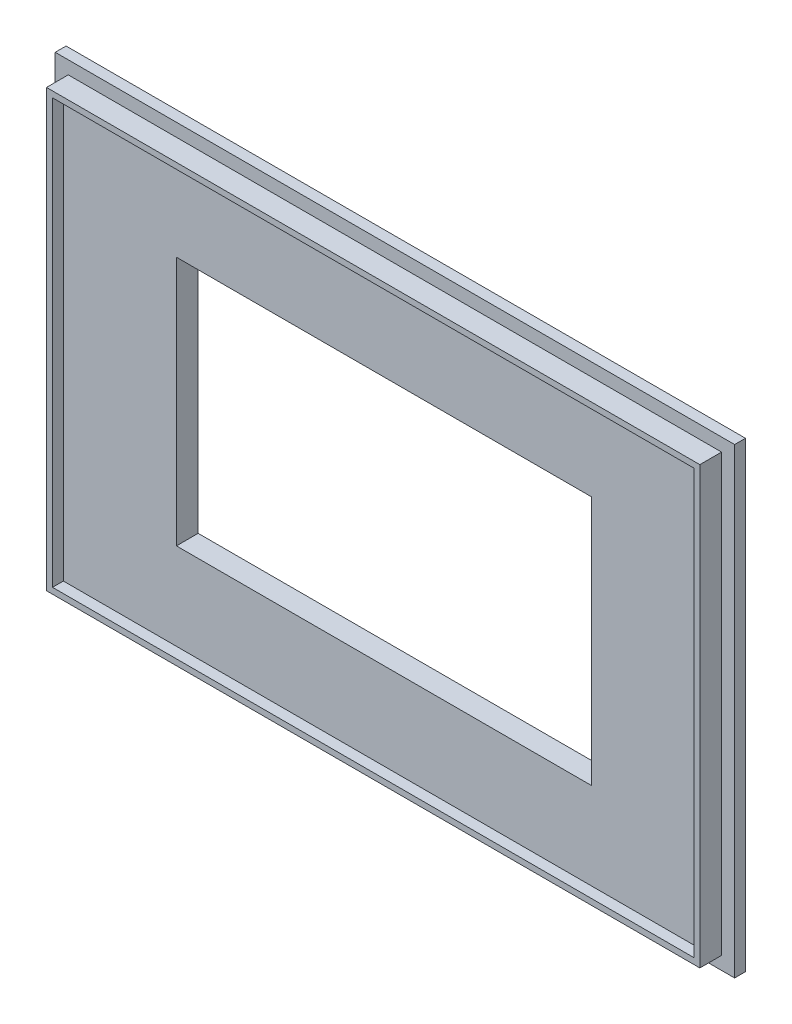
SolidWorks part; units mm, degrees
ref_plane "Front Plane" through (0, 0, 0) normal (0, 0, 1) x (1, 0, 0)
ref_plane "Top Plane" through (0, 0, 0) normal (0, 1, 0) x (1, 0, 0)
ref_plane "Right Plane" through (0, 0, 0) normal (1, 0, 0) x (0, 0, -1)
sketch "Sketch1" plane through (0, 0, 0) normal (0, 0, 1) x (1, 0, 0)
  line L1 (-79.375, -53.975) -> (79.375, -53.975)
  line L2 (-79.375, -53.975) -> (-79.375, 53.975)
  line L3 (-79.375, 53.975) -> (79.375, 53.975)
  line L4 (79.375, -53.975) -> (79.375, 53.975)
  line L5 (-79.375, -53.975) -> (79.375, 53.975) construction
  line L6 (-79.375, 53.975) -> (79.375, -53.975) construction
  point P0 (0, 0)
  dimension "D1" = 158.75
  dimension "D2" = 107.95
extrude "Boss-Extrude1" add sketch "Sketch1" along normal blind 2.54
sketch "Sketch2" plane through (0, 0, 2.54) normal (0, 0, 1) x (1, 0, 0)
  line L1 (-76.327, -50.927) -> (76.327, -50.927)
  line L2 (-76.327, -50.927) -> (-76.327, 50.927)
  line L3 (-76.327, 50.927) -> (76.327, 50.927)
  line L4 (76.327, -50.927) -> (76.327, 50.927)
  line L5 (-76.327, -50.927) -> (76.327, 50.927) construction
  line L6 (-76.327, 50.927) -> (76.327, -50.927) construction
  point P0 (0, 0)
  dimension "D1" = 152.654
  dimension "D2" = 101.854
extrude "Boss-Extrude2" add sketch "Sketch2" along normal blind 5.08 contours L2 L1 L4 L3
sketch "Sketch3" plane through (0, 0, 7.62) normal (0, 0, 1) x (1, 0, 0)
  line L1 (-74.93, -49.53) -> (74.93, -49.53)
  line L2 (-74.93, -49.53) -> (-74.93, 49.53)
  line L3 (-74.93, 49.53) -> (74.93, 49.53)
  line L4 (74.93, -49.53) -> (74.93, 49.53)
  line L5 (-74.93, -49.53) -> (74.93, 49.53) construction
  line L6 (-74.93, 49.53) -> (74.93, -49.53) construction
  point P0 (0, 0)
  dimension "D1" = 149.86
  dimension "D2" = 99.06
extrude "Cut-Extrude1" cut sketch "Sketch3" against normal blind 2.54
sketch "Sketch4" plane through (0, 0, 5.08) normal (0, 0, 1) x (1, 0, 0)
  line L1 (-48.514, -29.21) -> (48.514, -29.21)
  line L2 (-48.514, -29.21) -> (-48.514, 29.21)
  line L3 (-48.514, 29.21) -> (48.514, 29.21)
  line L4 (48.514, -29.21) -> (48.514, 29.21)
  line L5 (-48.514, -29.21) -> (48.514, 29.21) construction
  line L6 (-48.514, 29.21) -> (48.514, -29.21) construction
  point P0 (0, 0)
  dimension "D1" = 97.028
  dimension "D2" = 58.42
extrude "Cut-Extrude2" cut sketch "Sketch4" against normal through all
